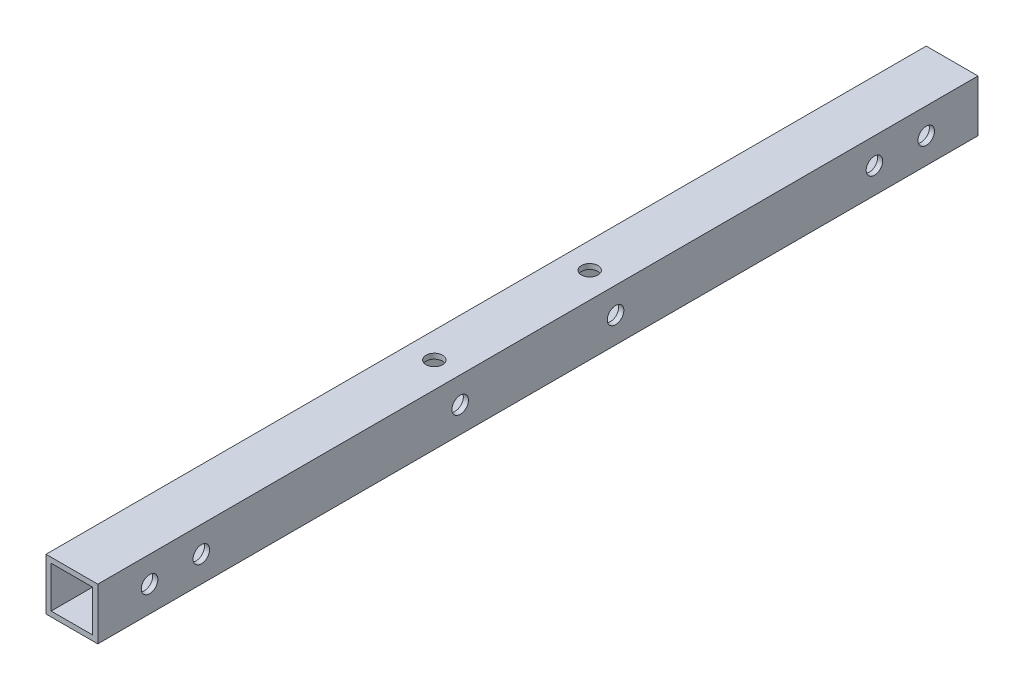
SolidWorks part; units mm, degrees
ref_plane "正面" through (0, 0, 0) normal (0, 0, 1) x (1, 0, 0)
ref_plane "平面" through (0, 0, 0) normal (0, 1, 0) x (1, 0, 0)
ref_plane "右側面" through (0, 0, 0) normal (1, 0, 0) x (0, 0, -1)
sketch "Sketch1" plane through (0, 0, 0) normal (0, 0, 1) x (1, 0, 0)
  line L1 (-5, 5) -> (5, 5)
  line L2 (-5, 5) -> (-5, -5)
  line L3 (-5, -5) -> (5, -5)
  line L4 (5, 5) -> (5, -5)
  line L5 (-5, 5) -> (5, -5) construction
  line L6 (-5, -5) -> (5, 5) construction
  line L7 (-4, 4) -> (4, 4)
  line L8 (-4, 4) -> (-4, -4)
  line L9 (-4, -4) -> (4, -4)
  line L10 (4, 4) -> (4, -4)
  line L11 (-4, 4) -> (4, -4) construction
  line L12 (-4, -4) -> (4, 4) construction
  point P0 (0, 0)
  point P6 (0, 0)
  dimension "D1" = 10
  dimension "D2" = 10
  dimension "D3" = 8
extrude "Boss-Extrude1" add sketch "Sketch1" along normal blind 170
sketch "Sketch2" plane through (5, 0, 0) normal (1, 0, 0) x (0, 0, -1)
  line L0 (-170, 0) -> (0, 0) construction
  line L1 (-170, -5) -> (-170, 5) construction
  line L2 (-85, 5) -> (-85, -5) construction
  line L3 (-170, 5) -> (0, 5) construction
  line L4 (-170, -5) -> (0, -5) construction
  line L5 (0, -5) -> (0, 5) construction
  circle A0 centre (-20, 0) radius 1.6
  circle A1 centre (-10, 0) radius 1.6
  circle A2 centre (-160, 0) radius 1.6
  circle A3 centre (-150, 0) radius 1.6
  circle A4 centre (-70, 0) radius 1.6
  circle A5 centre (-100, 0) radius 1.6
  dimension "D3" = 3.2
  dimension "D4" = 3.2
  dimension "D1" = 10
  dimension "D2" = 10
  dimension "D5" = 15
extrude "Cut-Extrude1" cut sketch "Sketch2" against normal up to surface (10 mm away) up to face at (-5, 0, 85)
sketch "Sketch3" plane through (0, 5, 0) normal (0, 1, 0) x (1, 0, 0)
  line L0 (0, 0) -> (0, -170) construction
  line L1 (5, -170) -> (-5, -170) construction
  line L2 (-5, -85) -> (5, -85) construction
  line L3 (-5, -170) -> (-5, 0) construction
  line L4 (5, -170) -> (5, 0) construction
  circle A0 centre (0, -70) radius 1.6
  circle A1 centre (0, -100) radius 1.6
  dimension "D1" = 3.2
  dimension "D2" = 15
extrude "Cut-Extrude2" cut sketch "Sketch3" against normal blind 10
